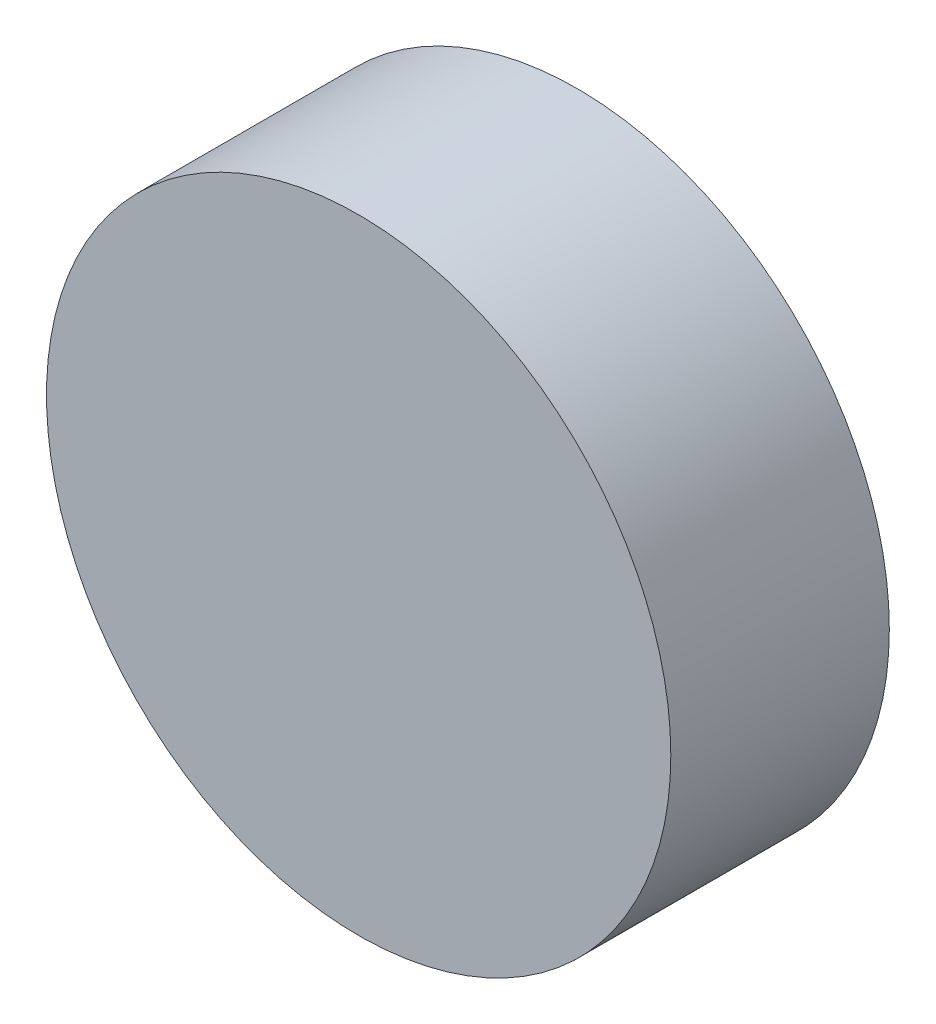
SolidWorks part; units mm, degrees
material "PET"
ref_plane "X-Y Datum" through (0, 0, 0) normal (0, 0, 1) x (1, 0, 0)
ref_plane "X-Z Datum" through (0, 0, 0) normal (0, 1, 0) x (1, 0, 0)
ref_plane "Y-Z Datum" through (0, 0, 0) normal (1, 0, 0) x (0, 0, -1)
sketch "Sketch1" plane through (0, 0, 0) normal (0, 0, 1) x (1, 0, 0)
  circle A0 centre (0, 0) radius 25.4
  circle A1 centre (0, 0) radius 23.876
  dimension "D1" = 50.8
  dimension "D2" = 47.752
extrude "Boss-Extrude1" add sketch "Sketch1" along normal blind 17.78
sketch "Sketch2" plane through (0, 0, 17.78) normal (0, 0, 1) x (1, 0, 0)
  circle A0 centre (0, 0) radius 23.876
extrude "Boss-Extrude2" add sketch "Sketch2" against normal blind 2.54
